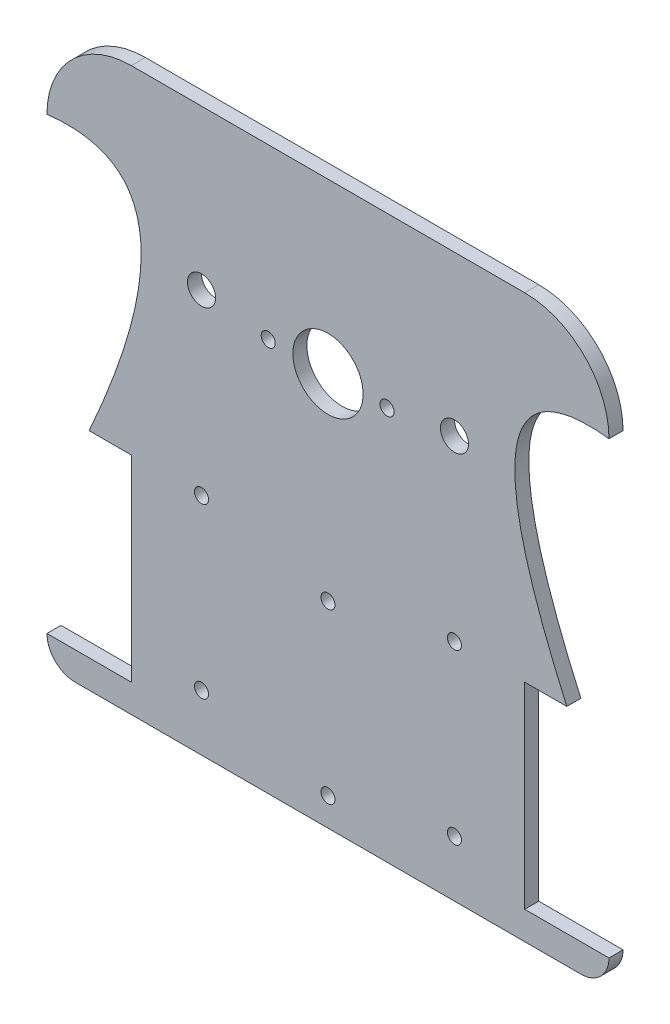
SolidWorks part; units mm, degrees
ref_plane "Front Plane" through (0, 0, 0) normal (0, 0, 1) x (1, 0, 0)
ref_plane "Top Plane" through (0, 0, 0) normal (0, 1, 0) x (1, 0, 0)
ref_plane "Right Plane" through (0, 0, 0) normal (1, 0, 0) x (0, 0, -1)
sketch "Sketch1" plane through (0, 0, 0) normal (0, 0, 1) x (1, 0, 0)
  line L1 (-90, -100) -> (90, -100)
  line L2 (-100, -90) -> (-100, 70)
  line L3 (-70, 100) -> (70, 100)
  line L4 (100, -90) -> (100, 70)
  arc A0 (90, -100) -> (100, -90) centre (90, -90) ccw
  arc A1 (-90, -100) -> (-100, -90) centre (-90, -90) cw
  arc A2 (70, 100) -> (100, 70) centre (70, 70) cw
  arc A3 (-100, 70) -> (-70, 100) centre (-70, 70) cw
  point P0 (0, 0)
  point P16 (100, -100)
  point P19 (-100, -100)
  point P23 (100, 100)
  point P26 (-100, 100)
  dimension "D6" = 10
  dimension "D7" = 10
  dimension "D8" = 30
  dimension "D9" = 30
  dimension "D1" = 200
  dimension "D2" = 200
  dimension "D10" = 100
  dimension "D11" = 100
extrude "Boss-Extrude1" add sketch "Sketch1" along normal blind 5
sketch "Sketch2" plane through (0, 0, 5) normal (0, 0, 1) x (1, 0, 0)
  line L0 (100, -20) -> (70, -20)
  line L1 (100, -90) -> (100, 70) construction
  line L2 (70, -20) -> (70, -90)
  line L3 (70, -90) -> (100, -90)
  line L4 (100, -90) -> (100, -20)
  line L5 (0, 100) -> (0, -100) construction
  line L6 (70, 100) -> (-70, 100) construction
  line L7 (-90, -100) -> (90, -100) construction
  line L8 (-70, -90) -> (-100, -90)
  line L9 (-70, -20) -> (-70, -90)
  line L10 (-100, -20) -> (-70, -20)
  line L11 (-100, -90) -> (-100, -20)
  dimension "D1" = 70
  dimension "D2" = 30
  dimension "D3" = 10
extrude "Cut-Extrude1" cut sketch "Sketch2" against normal blind 5
sketch "Sketch3" plane through (0, 0, 5) normal (0, 0, 1) x (1, 0, 0)
  line L0 (100, -20) -> (70, -20) construction
  line L1 (85, -20) -> (100, -20)
  line L2 (100, -20) -> (100, 70)
  line L3 (0, 100) -> (0, -100) construction
  line L4 (70, 100) -> (-70, 100) construction
  line L5 (-90, -100) -> (90, -100) construction
  line L6 (-85, -20) -> (-100, -20)
  line L7 (-100, -20) -> (-100, 70)
  spline S0 degree 2 poles (100, 70) (41.5628, 76.7696) (85, -20) knots 0 0 0 1 1 1
  spline S1 degree 2 poles (-100, 70) (-41.5628, 76.7696) (-85, -20) knots 0 0 0 1 1 1
extrude "Cut-Extrude2" cut sketch "Sketch3" against normal blind 5
sketch "Sketch5" plane through (0, 0, 5) normal (0, 0, 1) x (1, 0, 0)
  line L0 (-90, -100) -> (90, -100) construction
  line L1 (70, -20) -> (70, -90) construction
  line L2 (-70, -90) -> (-70, -20) construction
  line L3 (-45, -50) -> (39.8101, -50) construction
  line L4 (-45, -20) -> (-45, -17.5) construction
  line L5 (0, 0) -> (0, 61.3862) construction
  line L7 (-45, 38.351) -> (-45, 48.351) construction
  line L8 (-90, -100) -> (90, -100) construction
  circle A0 centre (45, -80) radius 2.5
  circle A1 centre (-45, -80) radius 2.5
  circle A2 centre (45, -20) radius 2.5
  circle A3 centre (-45, -20) radius 2.5
  circle A4 centre (-45, 43.351) radius 5
  circle A5 centre (45, 43.351) radius 5
  circle A6 centre (0, -30) radius 2.5
  dimension "D3" = 20
  dimension "D5" = 5
  dimension "D6" = 5
  dimension "D8" = 10
  dimension "D9" = 5
  dimension "D1" = 20
  dimension "D2" = 25
  dimension "D4" = 25
  dimension "D7" = 30
  dimension "D10" = 70
extrude "Cut-Extrude3" cut sketch "Sketch5" against normal blind 5
sketch "Sketch6" plane through (0, 0, 5) normal (0, 0, 1) x (1, 0, 0)
  line L0 (-90, -100) -> (90, -100) construction
  circle A0 centre (0, -90) radius 2.5
  dimension "D2" = 5
  dimension "D1" = 10
extrude "Cut-Extrude4" cut sketch "Sketch6" against normal blind 5
sketch "Sketch7" plane through (0, 0, 0) normal (0, 0, -1) x (-1, 0, 0)
  line L0 (70, -20) -> (-70, -20) construction
  line L1 (0, -20) -> (0, 40) construction
  line L2 (-70, 100) -> (70, 100) construction
  circle A0 centre (0, 40) radius 12.5
  circle A1 centre (-21, 40) radius 2.5
  circle A2 centre (21.26, 40) radius 2.5
  dimension "D2" = 25
  dimension "D5" = 5
  dimension "D6" = 5
  dimension "D1" = 60
  dimension "D3" = 21
  dimension "D4" = 21.26
extrude "Cut-Extrude5" cut sketch "Sketch7" against normal blind 5
